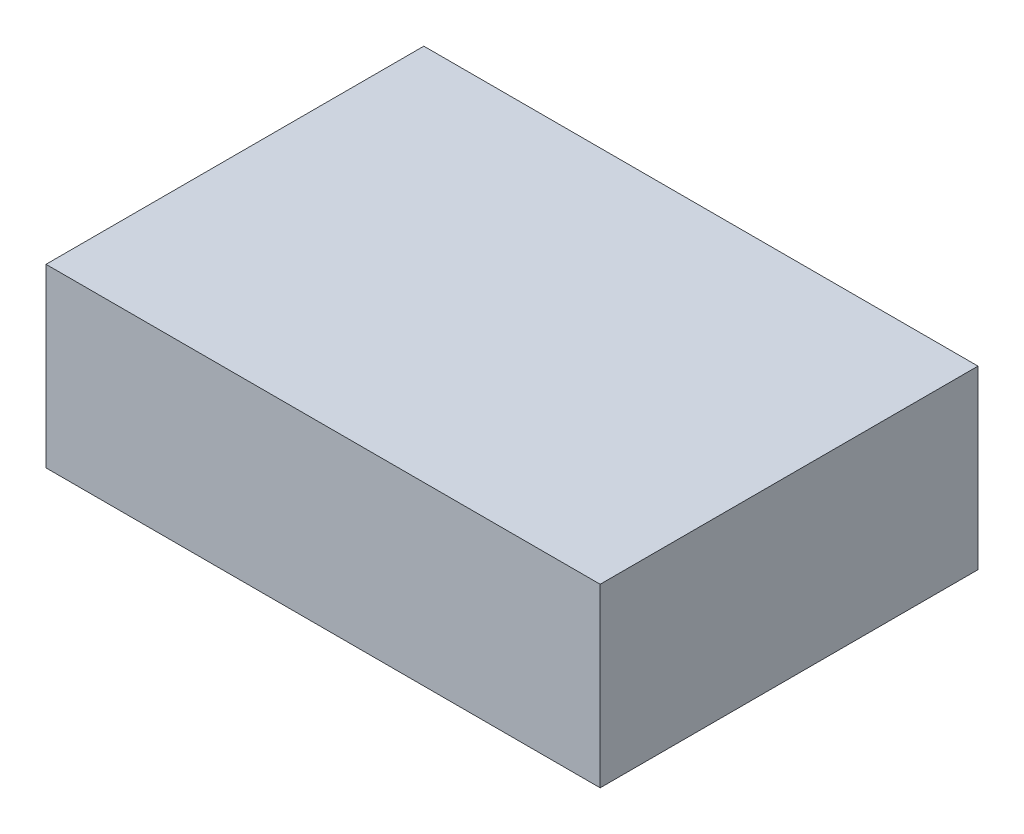
SolidWorks part; units mm, degrees
ref_plane "Front Plane" through (0, 0, 0) normal (0, 0, 1) x (1, 0, 0)
ref_plane "Top Plane" through (0, 0, 0) normal (0, 1, 0) x (1, 0, 0)
ref_plane "Right Plane" through (0, 0, 0) normal (1, 0, 0) x (0, 0, -1)
sketch "草圖1" plane through (0, 0, 0) normal (0, 0, 1) x (1, 0, 0)
  line L0 (-11, -3.5) -> (11, -3.5)
  line L1 (11, -3.5) -> (11, 3.5)
  line L2 (11, 3.5) -> (-11, 3.5)
  line L3 (-11, 3.5) -> (-11, -3.5)
extrude "填料-伸長1" add sketch "草圖1" along normal blind 15
